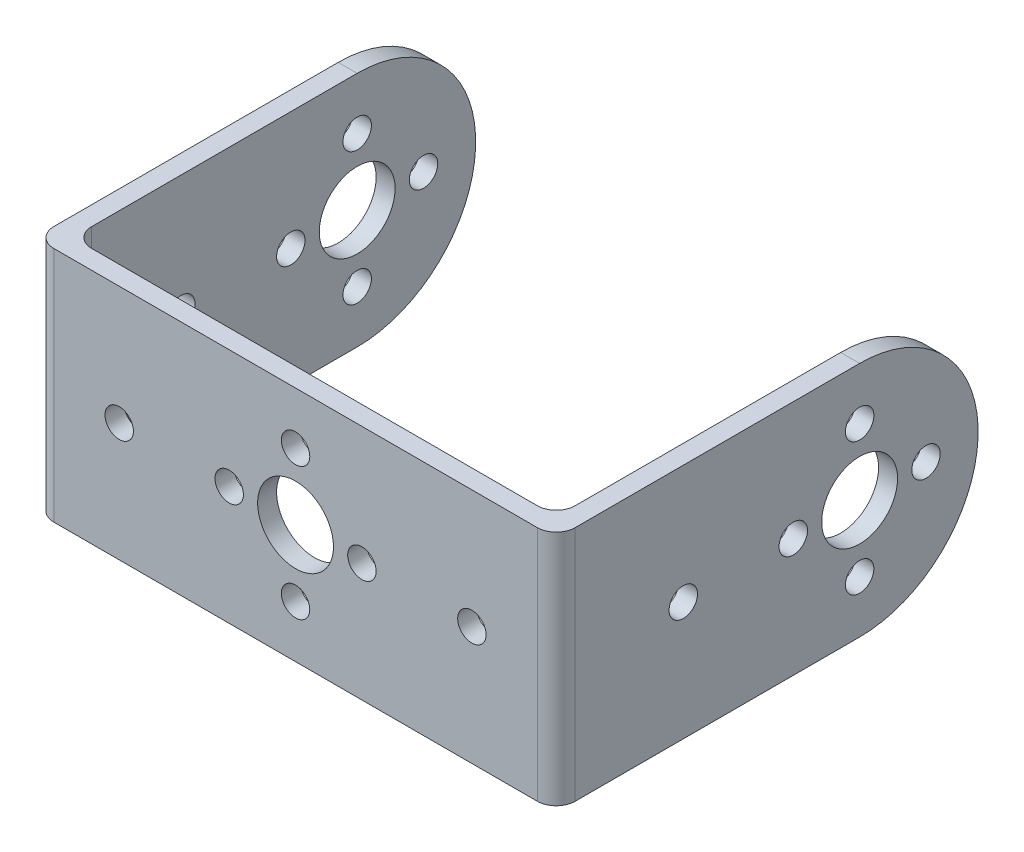
SolidWorks part; units mm, degrees
ref_plane "前视基准面" through (0, 0, 0) normal (0, 0, 1) x (1, 0, 0)
ref_plane "上视基准面" through (0, 0, 0) normal (0, 1, 0) x (1, 0, 0)
ref_plane "右视基准面" through (0, 0, 0) normal (1, 0, 0) x (0, 0, -1)
sketch "草图1" plane through (0, 0, 0) normal (0, 1, 0) x (1, 0, 0)
  line L0 (0, 0) -> (0, 34.1572) construction
  line L1 (0, 0) -> (27.5, 0)
  line L2 (27.5, 0) -> (27.5, 44.5)
  line L3 (27.5, 44.5) -> (25.5, 44.5)
  line L4 (25.5, 44.5) -> (25.5, 2)
  line L5 (25.5, 2) -> (0, 2)
  line L6 (0, 2) -> (0, 0)
  point P8 (26.5, 44.5)
  dimension "D1" = 2
  dimension "D2" = 2
  dimension "D3" = 55
  dimension "D4" = 44.5
extrude "凸台-拉伸1" add sketch "草图1" along normal blind 25
sketch "草图2" plane through (27.5, 0, 0) normal (1, 0, 0) x (0, 0, -1)
  line L0 (0, 12.5) -> (44.5, 12.5) construction
  line L1 (0, 25) -> (0, 0) construction
  line L2 (44.5, 25) -> (44.5, 0) construction
  line L3 (0, 0) -> (44.5, 0) construction
  line L4 (0, 25) -> (44.5, 25) construction
  circle A0 centre (32, 12.5) radius 7 construction
  circle A1 centre (32, 19.5) radius 1.5
  circle A2 centre (39, 12.5) radius 1.5
  circle A3 centre (32, 5.5) radius 1.5
  circle A4 centre (25, 12.5) radius 1.5
  circle A5 centre (32, 12.5) radius 4
  circle A6 centre (13.4, 12.5) radius 1.5
  arc A7 (32, 0) -> (32, 25) centre (32, 12.5) ccw
  line M7 (0, 0) -> (44.5, 0)
  line M8 (44.5, 0) -> (44.5, 25)
  line M9 (44.5, 25) -> (0, 25)
  dimension "D1" = 14
  dimension "D2" = 8
  dimension "D3" = 3
  dimension "D5" = 12.5
  dimension "D4" = 18.6
extrude "切除-拉伸1" cut sketch "草图2" against normal blind 25 contours A6 | A5 | A1 | A2 | A3 | A7 M7 M8 | A7 M8 M9 | A4
mirror "镜向1" about plane through (0, 25, -2) normal (1, 0, 0) of "切除-拉伸1", "凸台-拉伸1"
sketch "草图3" plane through (0, 0, 0) normal (0, 0, 1) x (1, 0, 0)
  line L0 (-27.5, 12.5) -> (27.5, 12.5) construction
  line L1 (-27.5, 25) -> (-27.5, 0) construction
  line L2 (27.5, 25) -> (27.5, 0) construction
  circle A0 centre (0, 12.5) radius 7 construction
  circle A1 centre (0, 19.5) radius 1.5
  circle A2 centre (7, 12.5) radius 1.5
  circle A3 centre (0, 5.5) radius 1.5
  circle A4 centre (-7, 12.5) radius 1.5
  circle A5 centre (-18.6, 12.5) radius 1.5
  circle A6 centre (0, 12.5) radius 4
  circle A7 centre (18.6, 12.5) radius 1.5
  dimension "D1" = 3
  dimension "D2" = 8
  dimension "D3" = 14
  dimension "D4" = 18.6
  dimension "D5" = 18.6
extrude "切除-拉伸2" cut sketch "草图3" against normal blind 25
fillet "圆角1" radius 2 4 edges at (25.5, 12.5, -2) (27.5, 12.5, 0) (-25.5, 12.5, -2) (-27.5, 12.5, 0)
